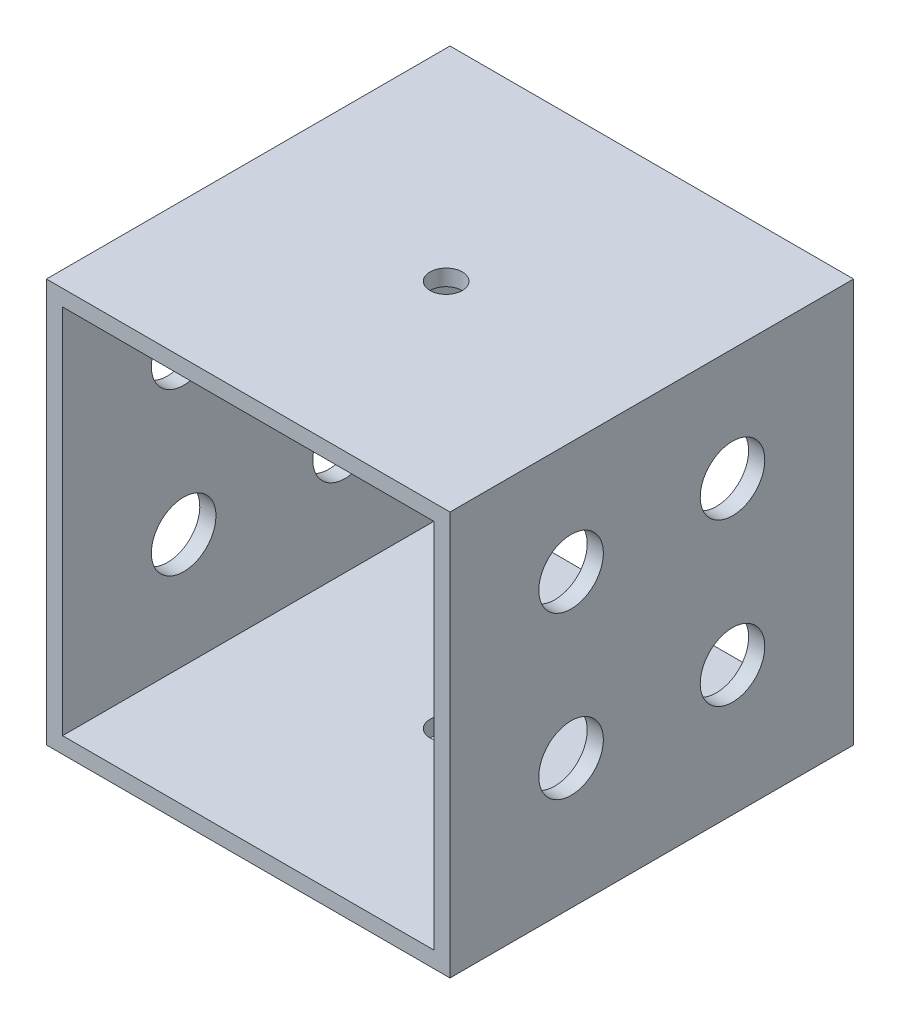
SolidWorks part; units mm, degrees
material "1060 Alloy"
ref_plane "Front Plane" through (0, 0, 0) normal (0, 0, 1) x (1, 0, 0)
ref_plane "Top Plane" through (0, 0, 0) normal (0, 1, 0) x (1, 0, 0)
ref_plane "Right Plane" through (0, 0, 0) normal (1, 0, 0) x (0, 0, -1)
sketch "Sketch1" plane through (0, 0, 0) normal (0, 0, 1) x (1, 0, 0)
  line L0 (-11.5, 11.5) -> (-11.5, -11.5)
  line L1 (-12.5, 12.5) -> (12.5, 12.5)
  line L2 (-12.5, 12.5) -> (-12.5, -12.5)
  line L3 (-12.5, -12.5) -> (12.5, -12.5)
  line L4 (12.5, 12.5) -> (12.5, -12.5)
  line L5 (-12.5, 12.5) -> (12.5, -12.5) construction
  line L6 (-12.5, -12.5) -> (12.5, 12.5) construction
  line L7 (-11.5, -11.5) -> (11.5, -11.5)
  line L8 (11.5, 11.5) -> (11.5, -11.5)
  line L9 (-11.5, 11.5) -> (11.5, 11.5)
  point P0 (0, 0)
  dimension "D1" = 25
  dimension "D2" = 25
  dimension "D3" = 1
extrude "Boss-Extrude1" add sketch "Sketch1" along normal blind 25
sketch "Sketch2" plane through (0, 12.5, 0) normal (0, 1, 0) x (1, 0, 0)
  circle A0 centre (0, -12.7388) radius 1
extrude "Cut-Extrude1" cut sketch "Sketch2" against normal blind 25
sketch "Sketch3" plane through (12.5, 0, 0) normal (1, 0, 0) x (0, 0, -1)
  line L0 (-25, -12.5) -> (-25, 12.5) construction
  circle A0 centre (-17.5, 5.5465) radius 2
  circle A1 centre (-7.5, 5.5465) radius 2
  circle A2 centre (-17.5, -4.4535) radius 2
  circle A3 centre (-7.5, -4.4535) radius 2
  point P10 (-17.5, -4.4535)
  point P11 (0, 0)
  dimension "D1" = 7.5
  dimension "D2" = 10
  dimension "D3" = 10
  dimension "D4" = 10
  dimension "D5" = 10
extrude "Cut-Extrude2" cut sketch "Sketch3" against normal blind 25
